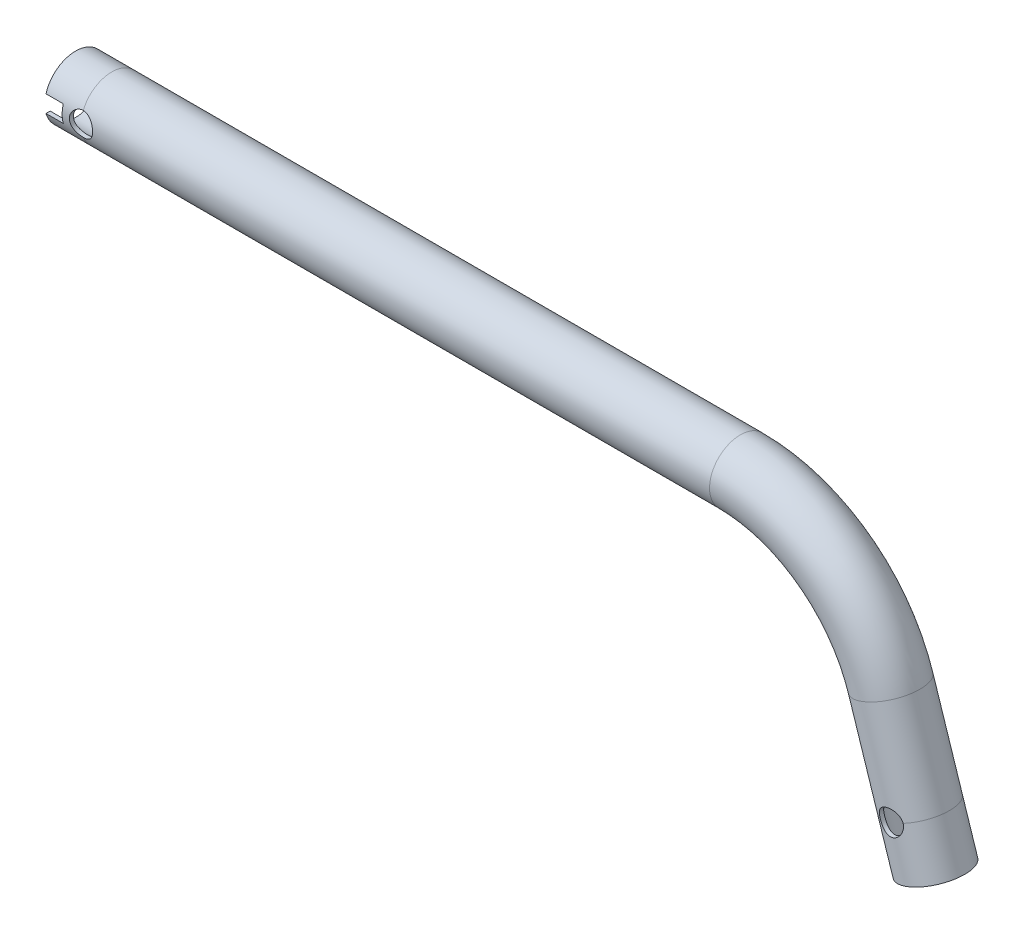
SolidWorks part; units mm, degrees
ref_plane "Front Plane" through (0, 0, 0) normal (0, 0, 1) x (1, 0, 0)
ref_plane "Top Plane" through (0, 0, 0) normal (0, 1, 0) x (1, 0, 0)
ref_plane "Right Plane" through (0, 0, 0) normal (1, 0, 0) x (0, 0, -1)
sketch "Sketch1" plane through (0, 0, 0) normal (0, 0, 1) x (1, 0, 0)
  line L0 (0, 0) -> (188.864, 0)
  line L1 (234.0392, -32.8217) -> (242.87, -60)
  line L2 (0, 0) -> (-10.8687, 0)
  line L3 (242.87, -60) -> (247.5053, -74.2658)
  arc A0 (234.0392, -32.8217) -> (188.864, 0) centre (188.864, -47.5) ccw
  point P10 (242.87, -60)
  dimension "D2" = 47.5
  dimension "D5" = 303
  dimension "D1" = 72
  dimension "D3" = 242.87
  dimension "D4" = 60
  dimension "D6" = 15
ref_plane "Plane1" through (-10.8687, 0, 0) normal (-1, 0, 0) x (0, 0, 1)
sketch "Sketch2" plane through (-10.8687, 0, 0) normal (-1, 0, 0) x (0, 0, 1)
  circle A0 centre (0, 0) radius 9.25
  circle A1 centre (0, 0) radius 8.05
  dimension "D1" = 1.2
  dimension "D2" = 18.5
sweep "Sweep1" add profiles "Sketch2" path "Sketch1"
sketch "Sketch3" plane through (0, 0, 0) normal (0, 0, 1) x (1, 0, 0)
  line L0 (234.0727, -62.8584) -> (251.6673, -57.1416) construction
  circle A4 centre (242.87, -60) radius 3.6
extrude "Cut-Extrude1" cut sketch "Sketch3" against normal up to next and the other way up to next
sketch "Sketch4" plane through (0, 0, 0) normal (0, 0, 1) x (1, 0, 0)
  line L0 (0, -9.25) -> (0, 9.25) construction
  circle A0 centre (0, 0) radius 3.5
  dimension "D1" = 7
extrude "Cut-Extrude2" cut sketch "Sketch4" along normal up to next
sketch "Sketch5" plane through (0, 0, 0) normal (0, 0, 1) x (1, 0, 0)
  line L0 (-10.8687, 0) -> (-10.8687, 2.555)
  line L1 (-10.8687, 9.25) -> (-10.8687, -9.25) construction
  line L2 (-10.8687, 2.555) -> (-5.6687, 2.555)
  line L3 (-5.6687, 2.555) -> (-5.6687, -2.555)
  line L4 (-5.6687, -2.555) -> (-10.8687, -2.555)
  line L5 (-10.8687, -2.555) -> (-10.8687, 0)
  dimension "D1" = 5.2
  dimension "D2" = 5.11
extrude "Cut-Extrude3" cut sketch "Sketch5" against normal through all and the other way through all
